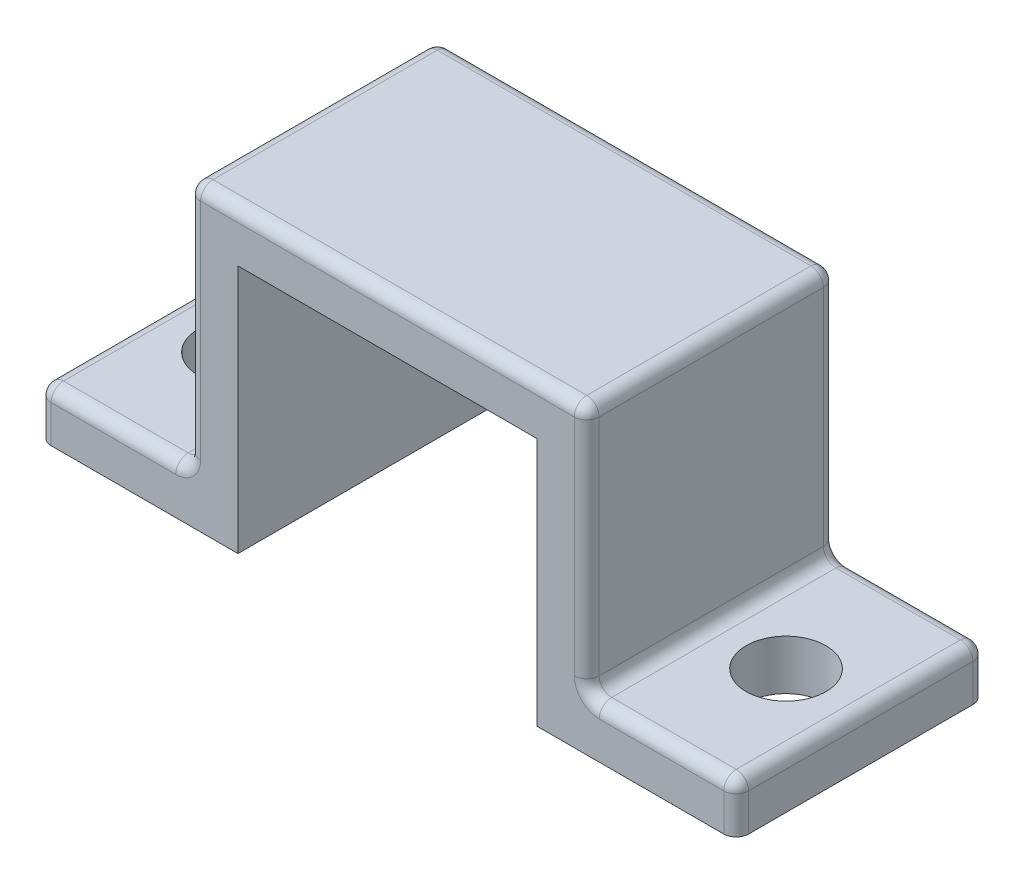
SolidWorks part; units mm, degrees
ref_plane "Ebene vorne" through (0, 0, 0) normal (0, 0, 1) x (1, 0, 0)
ref_plane "Ebene oben" through (0, 0, 0) normal (0, 1, 0) x (1, 0, 0)
ref_plane "Ebene rechts" through (0, 0, 0) normal (1, 0, 0) x (0, 0, -1)
sketch "Skizze1" plane through (0, 0, 0) normal (0, 0, 1) x (1, 0, 0)
  line L0 (0, -7.481) -> (0, 16.2911) construction
  line L1 (14, 0) -> (-14, 0)
  line L2 (-14, 0) -> (-14, 2)
  line L3 (-14, 2) -> (-8, 2)
  line L4 (-8, 2) -> (-8, 12)
  line L5 (-8, 12) -> (8, 12)
  line L6 (14, 0) -> (14, 2)
  line L7 (14, 2) -> (8, 2)
  line L8 (8, 2) -> (8, 12)
  point P10 (0, 12)
  point P11 (0, 0)
  dimension "D1" = 16
  dimension "D2" = 2
  dimension "D3" = 12
  dimension "D4" = 6
extrude "Grundkörper" add sketch "Skizze1" along normal blind 10
sketch "Skizze2" plane through (0, 0, 10) normal (0, 0, 1) x (1, 0, 0)
  line L0 (0, 12) -> (0, -2.8433) construction
  line L1 (8, 12) -> (-8, 12) construction
  line L2 (6, 10) -> (-6, 10)
  line L3 (-6, 10) -> (-6, 0)
  line L4 (-14, 0) -> (14, 0) construction
  line L5 (-6, 0) -> (6, 0)
  line L6 (6, 10) -> (6, 0)
  point P12 (0, 0)
  point P13 (0, 10)
  dimension "D1" = 10
  dimension "D2" = 12
extrude "Ausschnitt_Mitte" cut sketch "Skizze2" against normal through all
sketch "Skizze3" plane through (0, 2, 0) normal (0, 1, 0) x (1, 0, 0)
  line L0 (0, 0) -> (0, -12.96) construction
  line L1 (-14, -5) -> (16.1526, -5) construction
  line L2 (-14, -10) -> (-14, 0) construction
  line L3 (-11, 0) -> (-11, -10) construction
  line L4 (-8, 0) -> (-14, 0) construction
  line L5 (11, 0) -> (11, -10) construction
  circle A0 centre (-11, -5) radius 1.6
  circle A1 centre (11, -5) radius 1.6
  dimension "D1" = 3.2
  dimension "D2" = 22
extrude "Bohrungen" cut sketch "Skizze3" against normal through all
fillet "Verrundung1" radius 0.5 20 edges at (0, 12, 10) (-8, 12, 5) (0, 12, 0) (14, 2, 5) (11, 2, 10) (11, 2, 0) (8, 2, 5) (8, 7, 10) (8, 12, 5) (8, 7, 0) (14, 1, 0) (14, 1, 10) (-8, 2, 5) (-14, 1, 0) (-14, 1, 10) (-14, 2, 5) (-11, 2, 10) (-11, 2, 0) (-8, 7, 10) (-8, 7, 0)
